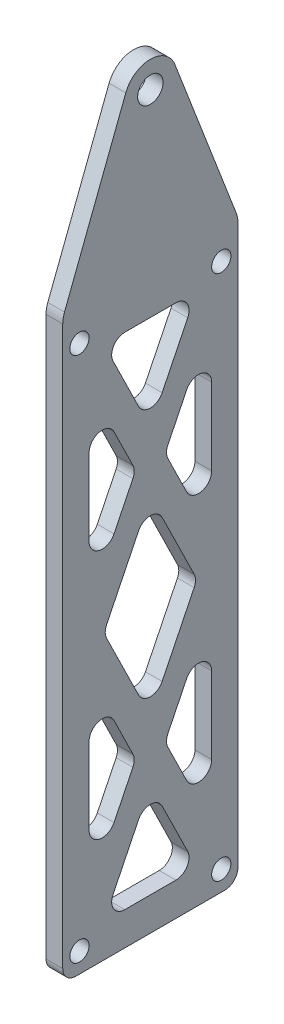
SolidWorks part; units mm, degrees
ref_plane "Front Plane" through (0, 0, 0) normal (0, 0, 1) x (1, 0, 0)
ref_plane "Top Plane" through (0, 0, 0) normal (0, 1, 0) x (1, 0, 0)
ref_plane "Right Plane" through (0, 0, 0) normal (1, 0, 0) x (0, 0, -1)
sketch "Sketch1" plane through (0, 0, 0) normal (1, 0, 0) x (0, 0, -1)
  line L0 (-13.4747, 0) -> (13.4747, 0) construction
  line L1 (0, 0) -> (0, 35) construction
  line L2 (-13.4747, 0) -> (0, 35) construction
  line L3 (0, 35) -> (13.4747, 0) construction
  line L4 (13.4747, 0) -> (-13.4747, 0) construction
  line L5 (20.7574, -5) -> (-20.7574, -5)
  line L6 (-20.7574, -5) -> (0, 48.9165)
  line L7 (0, 48.9165) -> (20.7574, -5)
  line L8 (-13.4747, 0) -> (13.4747, 0) construction
  line L9 (-13.4747, 0) -> (-13.4747, -100) construction
  line L10 (13.4747, 0) -> (13.4747, -100) construction
  line L11 (-13.4747, -100) -> (13.4747, -100) construction
  line L12 (-20.7574, -5) -> (20.7574, -5)
  line L13 (-20.7574, -5) -> (-20.7574, -103.81)
  line L14 (20.7574, -5) -> (20.7574, -103.81)
  line L15 (-20.7574, -103.81) -> (20.7574, -103.81)
  circle A0 centre (-13.4747, 0) radius 1.8288
  circle A1 centre (0, 35) radius 2.413
  circle A2 centre (13.4747, 0) radius 1.8288
  circle A3 centre (-13.4747, -100) radius 1.8288
  circle A4 centre (13.4747, -100) radius 1.8288
  point P4 (0, 0)
  dimension "D3" = 3.6576
  dimension "D4" = 4.826
  dimension "D1" = 26.9494
  dimension "D5" = 100
  dimension "D6" = 3.81
  dimension "D7" = 35
  dimension "D2" = 5
extrude "Boss-Extrude1" add sketch "Sketch1" along normal blind 3.175 contours L13 L15 L14 L5 A4 A3 | L7 L6 L5 A2 A1 A0
sketch "Sketch2" plane through (3.175, 0, 0) normal (1, 0, 0) x (0, 0, -1)
  line L3 (-11.645, -97.5) -> (-11.645, -2.5) construction
  line L4 (11.645, -97.5) -> (11.645, -2.5) construction
  line L5 (-11.645, -2.5) -> (11.645, -2.5) construction
  line L6 (-11.645, -97.5) -> (11.645, -97.5) construction
  line L7 (-20.7574, -5) -> (-20.7574, -103.81) construction
  line L8 (11.645, -97.5) -> (-11.645, -50) construction
  line L15 (11.645, -50) -> (-11.645, -50) construction
  line L24 (-16.645, -1051.4901) -> (-16.645, 48948.5099) construction
  line L25 (16.645, -1047.4882) -> (16.645, 48952.5118) construction
  line L26 (-20.7574, -5) -> (-16.645, -5) construction
  line L27 (20.7574, -5) -> (16.645, -5) construction
  line L28 (-16.645, -103.81) -> (-16.645, 37.413)
  line L29 (-16.645, -103.81) -> (-20.7574, -103.81)
  line L30 (-16.645, 37.413) -> (-20.7574, 37.413)
  line L31 (-20.7574, -103.81) -> (-20.7574, 37.413)
  line L32 (-20.7574, -103.81) -> (20.7574, -103.81) construction
  line L33 (16.645, -103.81) -> (16.645, 37.413)
  line L34 (16.645, -103.81) -> (20.7574, -103.81)
  line L35 (16.645, 37.413) -> (20.7574, 37.413)
  line L36 (20.7574, -103.81) -> (20.7574, 37.413)
  line L41 (-11.645, -97.5) -> (11.645, -50) construction
  line L42 (11.645, -50) -> (-11.645, -2.5) construction
  line L43 (11.645, -2.5) -> (-11.645, -50) construction
  line L44 (11.645, -91.8213) -> (-8.8607, -50)
  line L45 (11.645, -8.1787) -> (-8.8607, -50)
  line L46 (-8.8607, -97.5) -> (11.645, -55.6787)
  line L47 (11.645, -44.3213) -> (-8.8607, -2.5)
  line L48 (8.8607, -97.5) -> (-11.645, -55.6787)
  line L49 (8.8607, -2.5) -> (-11.645, -44.3213)
  line L50 (-11.645, -91.8213) -> (8.8607, -50)
  line L51 (8.8607, -50) -> (-11.645, -8.1787)
  line L52 (11.645, -91.8213) -> (11.645, -55.6787)
  line L53 (8.8607, -2.5) -> (-8.8607, -2.5)
  line L54 (-11.645, -8.1787) -> (-11.645, -44.3213)
  line L55 (-8.8607, -97.5) -> (8.8607, -97.5)
  line L56 (-13.8897, -96.3994) -> (8.8607, -50) construction
  line L57 (-9.4003, -98.6006) -> (14.4293, -50) construction
  line L58 (9.4003, -98.6006) -> (-14.4293, -50) construction
  line L59 (13.8897, -96.3994) -> (-8.8607, -50) construction
  line L60 (11.645, -44.3213) -> (11.645, -8.1787)
  line L61 (14.4293, -50) -> (-9.4003, -1.3994) construction
  line L62 (13.8897, -3.6006) -> (-8.8607, -50) construction
  line L63 (9.4003, -1.3994) -> (-14.4293, -50) construction
  line L64 (8.8607, -50) -> (-13.8897, -3.6006) construction
  line L65 (-11.645, -55.6787) -> (-11.645, -91.8213)
  circle A0 centre (13.4747, -100) radius 1.8288 construction
  circle A1 centre (13.4747, 0) radius 1.8288 construction
  circle A2 centre (0, 35) radius 2.413 construction
  point P0 (11.645, -50)
  point P2 (0, -97.5)
  point P28 (0, -50)
  line M9 (-20.7574, -5) -> (-20.7574, -103.81)
  line M11 (-20.7574, -103.81) -> (20.7574, -103.81)
  line M13 (20.7574, -103.81) -> (20.7574, -5)
  line M15 (20.7574, -5) -> (0, 48.9165)
  line M17 (0, 48.9165) -> (-20.7574, -5)
  dimension "D4" = 2.5
  dimension "D1" = 33.29
  dimension "D2" = 5
  dimension "D3" = 2.5
  dimension "D5" = 2.5
  dimension "D6" = 2.5
  dimension "D8" = 5
extrude "Cut-Extrude1" cut sketch "Sketch2" against normal through all contours L33 M11 M13 M15 | L28 M11 M17 M9 | L48 L65 L50 | L46 L55 L48 | L44 L52 L46 | L50 L51 L45 L44 | L47 L60 L45 | L51 L54 L49 | L49 L53 L47
fillet "Fillet1" radius 2.5 24 edges at (1.5875, -103.81, 16.645) (1.5875, -103.81, -16.645) (1.5875, -44.3213, -11.645) (1.5875, -20.5713, 0) (1.5875, -50, -8.8607) (1.5875, -73.75, 2.7843) (1.5875, -2.5, -8.8607) (1.5875, -26.25, 2.7843) (1.5875, -31.9287, 0) (1.5875, -55.6787, -11.645) (1.5875, -8.1787, -11.645) (1.5875, -8.1787, 11.645) (1.5875, -55.6787, 11.645) (1.5875, -2.5, 8.8607) (1.5875, -26.25, -2.7843) (1.5875, -50, 8.8607) (1.5875, -73.75, -2.7843) (1.5875, -91.8213, -11.645) (1.5875, -68.0713, 0) (1.5875, -44.3213, 11.645) (1.5875, -91.8213, 11.645) (1.5875, -79.4287, 0) (1.5875, -97.5, -8.8607) (1.5875, -97.5, 8.8607)
fillet "Fillet2" radius 5 3 edges at (1.5875, 48.9165, 0) (1.5875, 5.6818, 16.645) (1.5875, 5.6818, -16.645)
